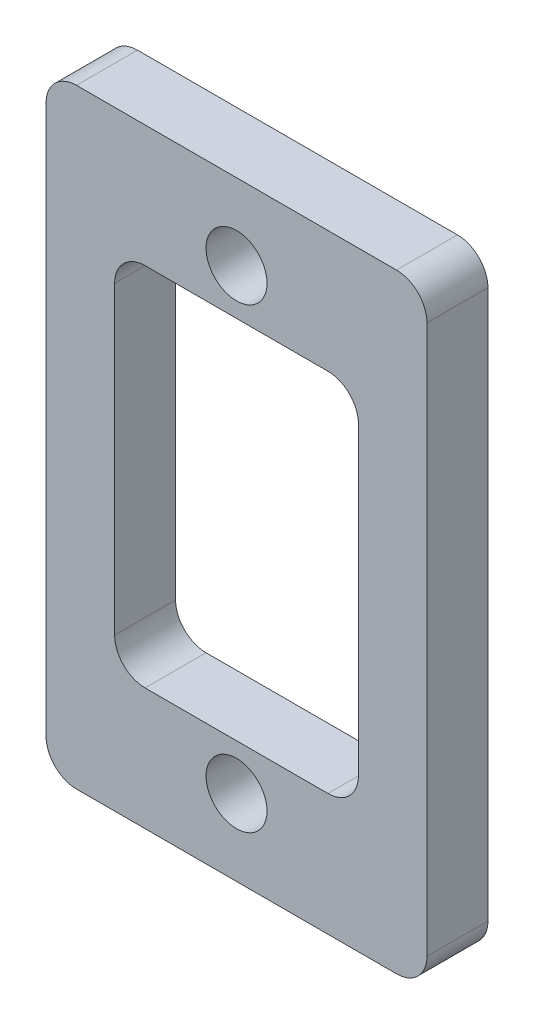
SolidWorks part; units mm, degrees
material "Thornel Mat VMA"
ref_plane "前视基准面" through (0, 0, 0) normal (0, 0, 1) x (1, 0, 0)
ref_plane "上视基准面" through (0, 0, 0) normal (0, 1, 0) x (1, 0, 0)
ref_plane "右视基准面" through (0, 0, 0) normal (1, 0, 0) x (0, 0, -1)
sketch "草图1" plane through (0, 0, 0) normal (0, 0, 1) x (1, 0, 0)
  line L1 (-12.5, -20) -> (12.5, -20)
  line L2 (-12.5, -20) -> (-12.5, 20)
  line L3 (-12.5, 20) -> (12.5, 20)
  line L4 (12.5, -20) -> (12.5, 20)
  line L5 (0, 20) -> (0, -20) construction
  line L6 (-12.5, 0) -> (12.5, 0) construction
  point P0 (0, 0)
  dimension "D1" = 40
  dimension "D2" = 25
extrude "凸台-拉伸1" add sketch "草图1" along normal blind 4
sketch "草图2" plane through (0, 0, 4) normal (0, 0, 1) x (1, 0, 0)
  line L0 (0, -15) -> (0, 15) construction
  circle A0 centre (0, 15) radius 2
  circle A1 centre (0, -15) radius 2
  point P4 (0, 0)
  dimension "D2" = 4
  dimension "D1" = 30
extrude "切除-拉伸1" cut sketch "草图2" against normal blind 10
fillet "圆角1" radius 2 4 edges at (12.5, -20, 2) (-12.5, -20, 2) (-12.5, 20, 2) (12.5, 20, 2)
sketch "草图3" plane through (0, 0, 4) normal (0, 0, 1) x (1, 0, 0)
  line L0 (12.5, -18) -> (12.5, 18) construction
  line L1 (-8, -12) -> (8, -12)
  line L2 (-8, -12) -> (-8, 12)
  line L3 (-8, 12) -> (8, 12)
  line L4 (8, -12) -> (8, 12)
  line L5 (0, 12) -> (0, -12) construction
  line L6 (-8, 0) -> (8, 0) construction
  circle A0 centre (0, 15) radius 2 construction
  point P0 (0, 0)
  dimension "D1" = 3
  dimension "D2" = 4.5
extrude "切除-拉伸2" cut sketch "草图3" against normal blind 10
fillet "圆角2" radius 2 4 edges at (-8, 12, 2) (8, 12, 2) (8, -12, 2) (-8, -12, 2)
